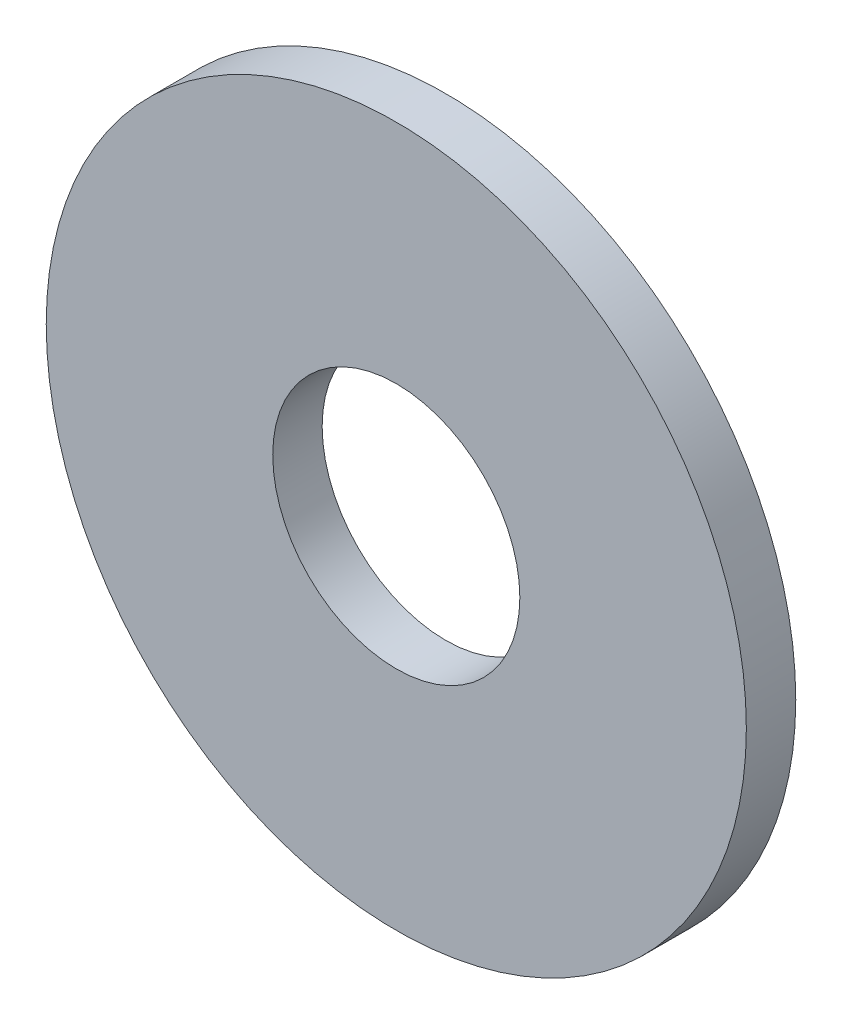
SolidWorks part; units mm, degrees
ref_plane "Front Plane" through (0, 0, 0) normal (0, 0, 1) x (1, 0, 0)
ref_plane "Top Plane" through (0, 0, 0) normal (0, 1, 0) x (1, 0, 0)
ref_plane "Right Plane" through (0, 0, 0) normal (1, 0, 0) x (0, 0, -1)
sketch "Sketch1" plane through (0, 0, 0) normal (0, 0, 1) x (1, 0, 0)
  circle A0 centre (0, 0) radius 42.5
  circle A1 centre (0, 0) radius 15
  dimension "D1" = 85
  dimension "D2" = 30
extrude "Boss-Extrude1" add sketch "Sketch1" along normal blind 6
